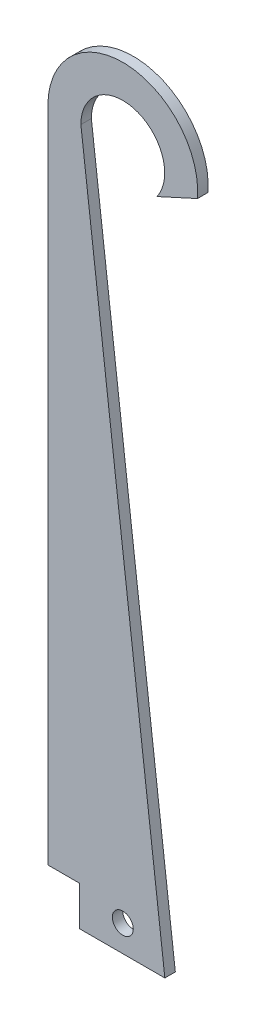
SolidWorks part; units mm, degrees
ref_plane "Front Plane" through (0, 0, 0) normal (0, 0, 1) x (1, 0, 0)
ref_plane "Top Plane" through (0, 0, 0) normal (0, 1, 0) x (1, 0, 0)
ref_plane "Right Plane" through (0, 0, 0) normal (1, 0, 0) x (0, 0, -1)
sketch "Sketch1" plane through (0, 0, 0) normal (0, 0, 1) x (1, 0, 0)
  line L0 (-17.3574, -1.7396) -> (-17.3574, 404.6604) construction
  line L1 (3.3311, 389.9246) -> (27.9099, 401.1627)
  line L2 (-62.7596, 404.6604) -> (-62.7596, 6.0902)
  line L5 (-43.7153, -17.7858) -> (-43.7153, 6.0902)
  line L6 (-43.7153, 6.0902) -> (-62.7596, 6.0902)
  line L7 (-42.7574, 404.6604) -> (8.1257, -17.7858)
  line L8 (8.1257, -17.7858) -> (-43.7153, -17.7858)
  circle A0 centre (-17.3574, 404.6604) radius 25.4 construction
  arc A1 (8.0426, 404.6604) -> (-42.7574, 404.6604) centre (-17.3574, 404.6604) ccw
  arc A2 (8.0426, 404.6604) -> (3.3311, 389.9246) centre (-17.3574, 404.6604) cw
  arc A3 (27.9099, 401.1627) -> (-62.7596, 404.6604) centre (-17.3574, 404.6604) ccw
  circle A4 centre (-17.3574, -1.7396) radius 6.35
  point P2 (0, 0)
  point P5 (-62.7596, 404.6604)
  point P13 (-55.0151, 402.3237)
  point P14 (-50.0175, 403.9134)
  point P15 (21.5884, 400.9046)
  point P16 (22.5411, 398.4346)
  point P18 (0, 0)
  dimension "D2" = 50.8
  dimension "D3" = 12.7
  dimension "D5" = 23.876
  dimension "D1" = 406.4
  dimension "D6" = 19.0443
extrude "Boss-Extrude1" add sketch "Sketch1" along normal blind 6.35
